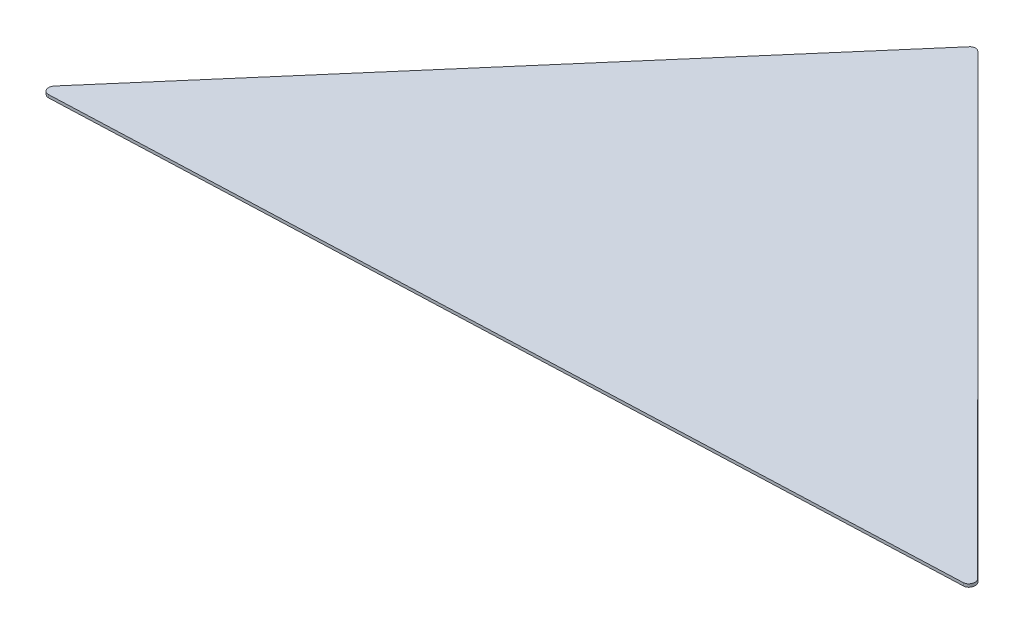
SolidWorks part; units mm, degrees
ref_plane "Front Plane" through (0, 0, 0) normal (0, 0, 1) x (1, 0, 0)
ref_plane "Top Plane" through (0, 0, 0) normal (0, 1, 0) x (1, 0, 0)
ref_plane "Right Plane" through (0, 0, 0) normal (1, 0, 0) x (0, 0, -1)
sketch "Sketch2" plane through (75.2093, -1945.5005, -70.5625) normal (-0.0386, 0.9986, 0.0362) x (0.9993, 0.0386, 0.0007)
  line L3 (121.6618, 916.7448) -> (-185.9777, 609.5105)
  line L4 (-183.1511, 602.6802) -> (431.7227, 602.6802)
  line L5 (434.5511, 609.5087) -> (127.3168, 916.743)
  arc A0 (431.7227, 602.6802) -> (434.5511, 609.5087) centre (431.7227, 606.6802) ccw
  arc A1 (-185.9777, 609.5105) -> (-183.1511, 602.6802) centre (-183.1511, 606.6802) ccw
  arc A2 (121.6618, 916.7448) -> (127.3168, 916.743) centre (124.4884, 913.9145) cw
  dimension "D1" = 4
extrude "Boss-Extrude1" add sketch "Sketch2" along normal blind 2 contours L3 A1 L4 A0 L5 A2
